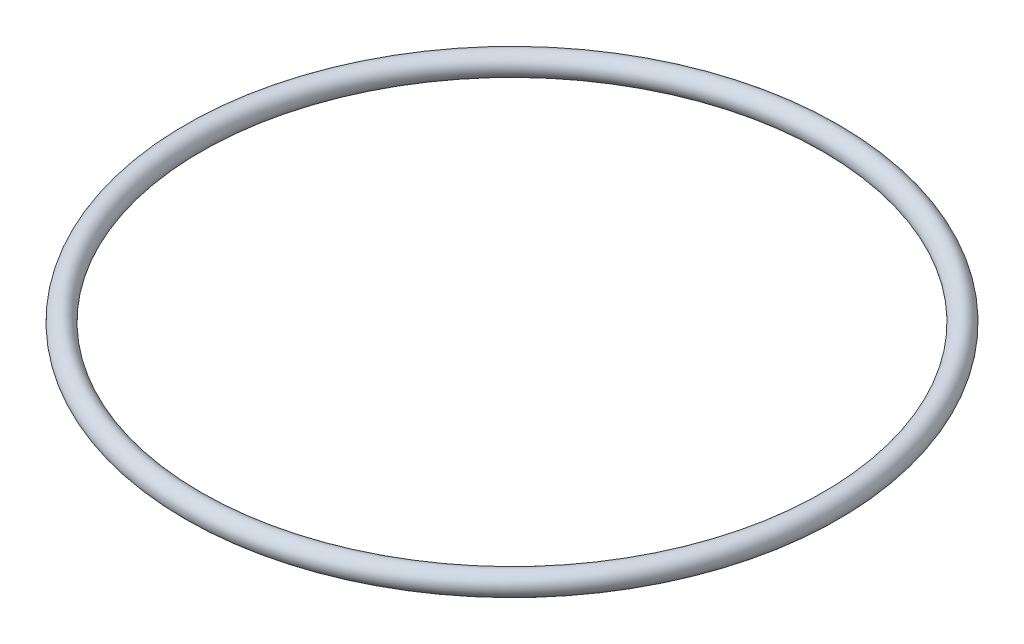
SolidWorks part; units mm, degrees
material "Silicon Rubber"
ref_plane "Front Plane" through (0, 0, 0) normal (0, 0, 1) x (1, 0, 0)
ref_plane "Top Plane" through (0, 0, 0) normal (0, 1, 0) x (1, 0, 0)
ref_plane "Right Plane" through (0, 0, 0) normal (1, 0, 0) x (0, 0, -1)
sketch "Sketch1" plane through (0, 0, 0) normal (0, 0, 1) x (1, 0, 0)
  line L0 (0, 0) -> (0, 5.0672) construction
  line L1 (0, 0) -> (-46.0375, 0) construction
  circle A0 centre (-46.0375, 0) radius 1.5875
  dimension "D1" = 3.175
  dimension "D2" = 46.0375
revolve "Revolve1" add sketch "Sketch1" angle 360 about L0
